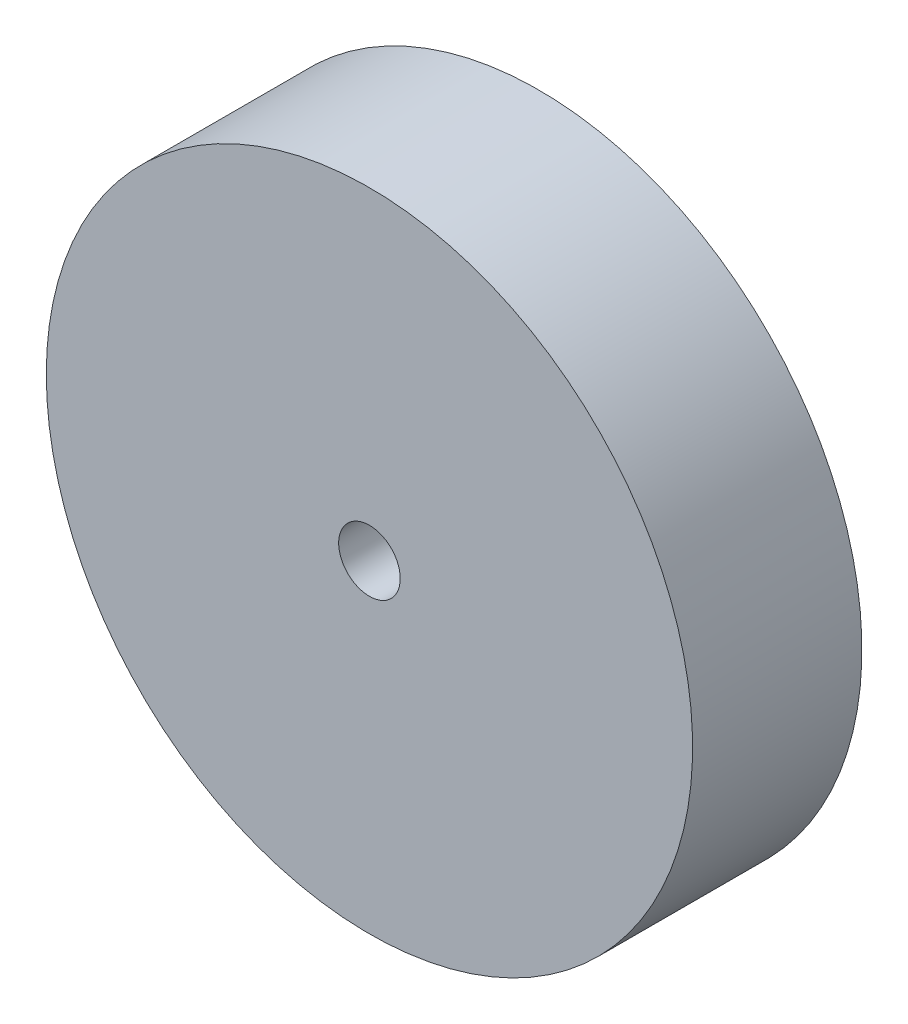
SolidWorks part; units mm, degrees
ref_plane "Front Plane" through (0, 0, 0) normal (0, 0, 1) x (1, 0, 0)
ref_plane "Top Plane" through (0, 0, 0) normal (0, 1, 0) x (1, 0, 0)
ref_plane "Right Plane" through (0, 0, 0) normal (1, 0, 0) x (0, 0, -1)
sketch "Sketch1" plane through (0, 0, 0) normal (0, 0, 1) x (1, 0, 0)
  circle A0 centre (0, 0) radius 88
extrude "Boss-Extrude3" add sketch "Sketch1" along normal blind 25
sketch "Sketch4" plane through (0, 0, 25) normal (0, 0, 1) x (1, 0, 0)
  line L0 (0, 88) -> (0, 100) construction
  line L1 (5.236, 100) -> (-5.236, 100)
  line L2 (-5.236, 100) -> (-5.236, 86.6488)
  line L3 (-5.236, 86.6488) -> (5.236, 86.6488)
  line L4 (5.236, 86.6488) -> (5.236, 100)
  circle A0 centre (0, 0) radius 88 construction
  point P9 (0, 100)
extrude "Boss-Extrude4" add sketch "Sketch4" against normal blind 25
fillet "Fillet2" radius 4 4 edges at (-5.236, 100, 12.5) (0, 100, 0) (5.236, 100, 12.5) (0, 100, 25)
pattern_circular "CirPattern1" count 30 over 360 about axis through (0, 0.3177, 0) along (0, 0, 1) of "Fillet2", "Boss-Extrude4"
ref_plane "Plane1" through (-5.236, 96, 25) normal (-1, 0, 0) x (0, 0, 1)
sketch "Sketch6" plane through (0, 0, 25) normal (0, 0, 1) x (1, 0, 0)
  circle A0 centre (0, 0) radius 10
extrude "Boss-Extrude5" add sketch "Sketch6" along normal blind 60
sketch "Sketch7" plane through (0, 0, 0) normal (0, 0, -1) x (-1, 0, 0)
  circle A0 centre (0, 0) radius 10
extrude "Boss-Extrude6" add sketch "Sketch7" along normal blind 10
sketch "Sketch8" plane through (0, 0, 85) normal (0, 0, 1) x (1, 0, 0)
  circle A0 centre (0, 0) radius 10
extrude "Boss-Extrude7" add sketch "Sketch8" along normal blind 10
sketch "Sketch9" plane through (0, 0, 95) normal (0, 0, 1) x (1, 0, 0)
  circle A0 centre (0, 0) radius 10
extrude "Boss-Extrude8" add sketch "Sketch9" along normal blind 25
sketch "Sketch10" plane through (0, 0, 120) normal (0, 0, 1) x (1, 0, 0)
  circle A0 centre (0, 0) radius 10
extrude "Boss-Extrude9" add sketch "Sketch10" along normal blind 42.5
sketch "Sketch12" plane through (0, 0, 162.5) normal (0, 0, 1) x (1, 0, 0)
  circle A0 centre (0, 0) radius 12.5
extrude "Cut-Extrude1" cut sketch "Sketch12" against normal blind 12
sketch "Sketch13" plane through (0, 0, 150.5) normal (0, 0, 1) x (1, 0, 0)
  circle A0 centre (0, 0) radius 10
extrude "Cut-Extrude2" cut sketch "Sketch13" against normal blind 55.5
sketch "Sketch14" plane through (0, 0, 95) normal (0, 0, 1) x (1, 0, 0)
  circle A0 centre (0, 0) radius 10
extrude "Boss-Extrude10" add sketch "Sketch14" along normal blind 440
sketch "Sketch15" plane through (0, 0, 0) normal (0, 0, -1) x (-1, 0, 0)
  circle A0 centre (0, 0) radius 105
extrude "Boss-Extrude12" add sketch "Sketch15" against normal blind 25
sketch "Sketch16" plane through (0, 0, 0) normal (0, 0, -1) x (-1, 0, 0)
  circle A0 centre (0, 0) radius 105
extrude "Boss-Extrude13" add sketch "Sketch16" along normal blind 30
sketch "Sketch17" plane through (0, 0, 535) normal (0, 0, 1) x (1, 0, 0)
  circle A0 centre (0, 0) radius 10
extrude "Boss-Extrude14" add sketch "Sketch17" along normal blind 50
sketch "Sketch18" plane through (0, 0, 585) normal (0, 0, 1) x (1, 0, 0)
  circle A0 centre (0, 0) radius 10
extrude "Cut-Extrude3" cut sketch "Sketch18" against normal blind 700
